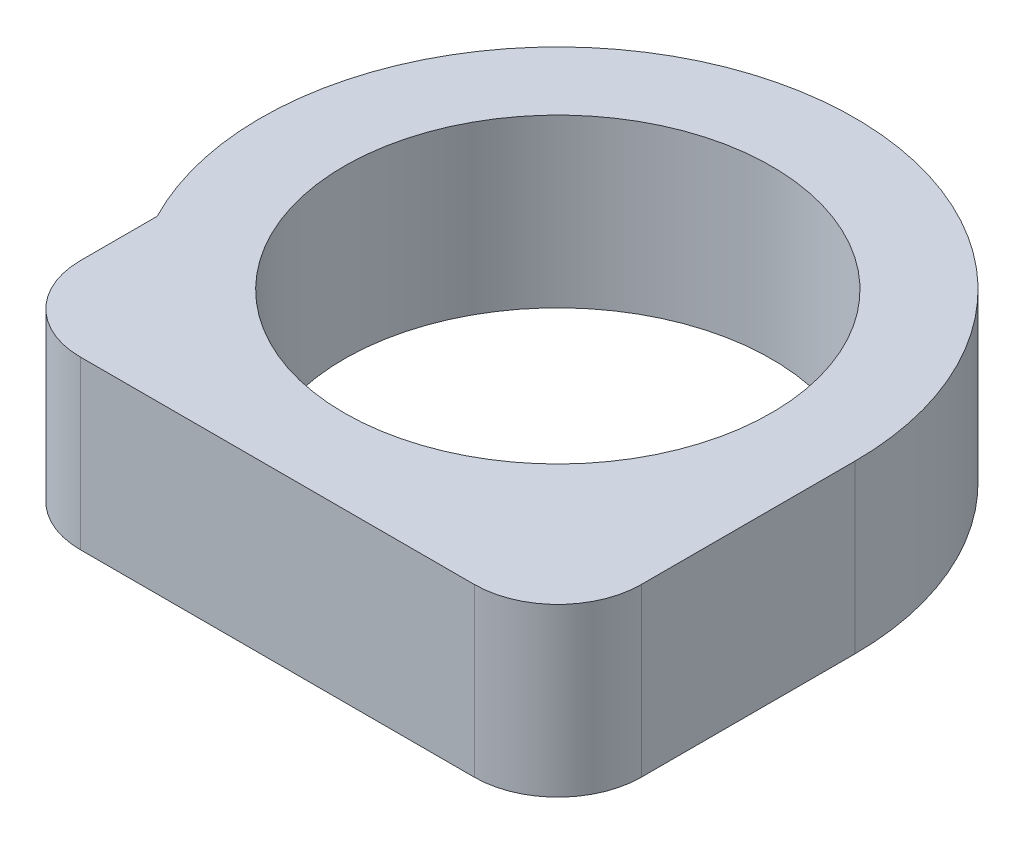
SolidWorks part; units mm, degrees
ref_plane "Front Plane" through (0, 0, 0) normal (0, 0, 1) x (1, 0, 0)
ref_plane "Top Plane" through (0, 0, 0) normal (0, 1, 0) x (1, 0, 0)
ref_plane "Right Plane" through (0, 0, 0) normal (1, 0, 0) x (0, 0, -1)
sketch "Sketch1" plane through (0, 0, 0) normal (0, 1, 0) x (1, 0, 0)
  line L1 (-18.5125, 1.616) -> (15.0875, 1.616)
  line L2 (-18.5125, 1.616) -> (-18.5125, -16.184)
  line L3 (-18.5125, -16.184) -> (15.0875, -16.184)
  line L4 (15.0875, 1.616) -> (15.0875, -16.184)
  circle A0 centre (-2.7125, 1.616) radius 12.8
  circle A1 centre (-2.7125, 1.616) radius 17.8
  dimension "D1" = 25.6
  dimension "D2" = 5
  dimension "D3" = 0
  dimension "D4" = 15.8
  dimension "D5" = 17.8
  dimension "D6" = 17.8
extrude "Boss-Extrude2" add sketch "Sketch1" along normal blind 10 contours A1 L1 A0 | L1 A1 A0 | A1 L3 L4 | A1 L2 L3
fillet "Fillet1" radius 5 2 edges at (-18.5125, 5, 16.184) (15.0875, 5, 16.184)
equation "\"w1\"= ( 21.68 + 21.52 ) / 2"
equation "\"w2\"= ( 19.35 + 19.57 ) / 2"
equation "\"w3\"= 17.03"
equation "\"w4\"= ( 15.09 + 15.18 ) / 2"
equation "\"w5\"= 13.2"
equation "\"w6\"= ( 11.13 + 11.42 ) / 2"
equation "\"w7\"= 9.3"
equation "\"mount_height\" = 20"
equation "\"mount_thickness\"= 5"
equation "\"D1@Sketch1\" = \"w1\" + \"tolerance\""
equation "\"D2@Sketch1\"=\"mount_thickness\""
equation "\"webcam depth\"= 40.4"
equation "\"D6@Sketch1\"=\"D1@Sketch1\"/2+\"D2@Sketch1\""
equation "\"D5@Sketch1\"=\"D6@Sketch1\""
equation "\"tolerance\"= 4"
